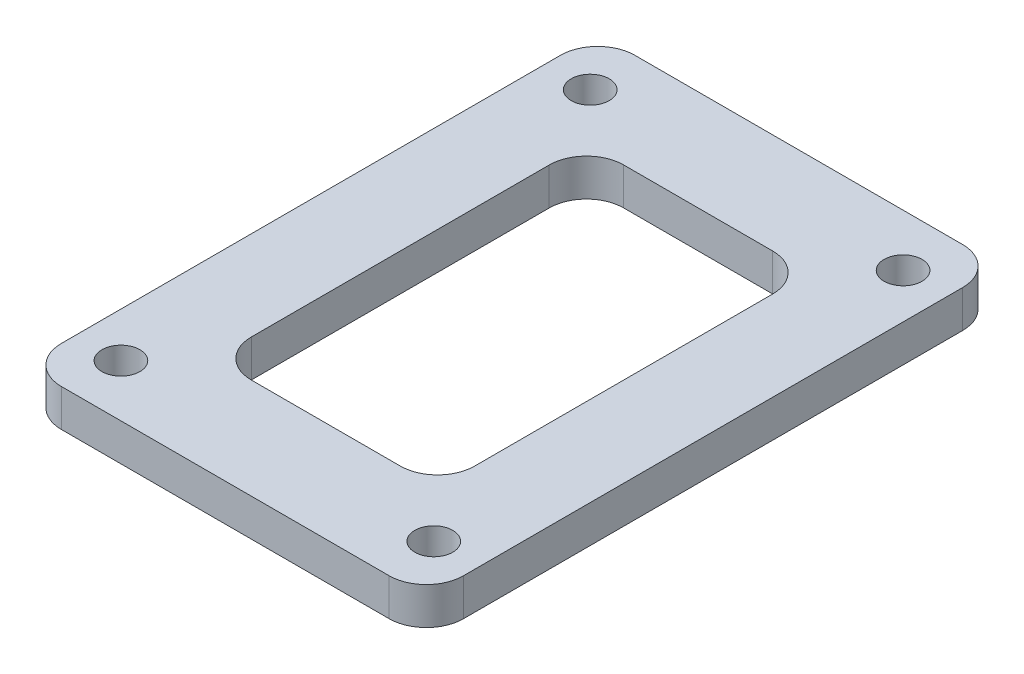
SolidWorks part; units mm, degrees
ref_plane "Front Plane" through (0, 0, 0) normal (0, 0, 1) x (1, 0, 0)
ref_plane "Top Plane" through (0, 0, 0) normal (0, 1, 0) x (1, 0, 0)
ref_plane "Right Plane" through (0, 0, 0) normal (1, 0, 0) x (0, 0, -1)
sketch "Sketch1" plane through (0, 0, 0) normal (0, 1, 0) x (1, 0, 0)
  line L1 (-27, 38.5) -> (27, 38.5)
  line L2 (-27, 38.5) -> (-27, -38.5)
  line L3 (-27, -38.5) -> (27, -38.5)
  line L4 (27, 38.5) -> (27, -38.5)
  line L5 (-27, 38.5) -> (27, -38.5) construction
  line L6 (-27, -38.5) -> (27, 38.5) construction
  point P0 (0, 0)
  dimension "D1" = 54
  dimension "D2" = 77
extrude "Boss-Extrude1" add sketch "Sketch1" along normal blind 5
sketch "Sketch2" plane through (0, 5, 0) normal (0, 1, 0) x (1, 0, 0)
  line L0 (27, 38.5) -> (-27, 38.5) construction
  line L1 (0, 38.5) -> (0, -38.5) construction
  line L2 (-27, -38.5) -> (27, -38.5) construction
  line L3 (-27, 0) -> (27, 0) construction
  line L4 (-27, 38.5) -> (-27, -38.5) construction
  line L5 (27, -38.5) -> (27, 38.5) construction
  circle A0 centre (-21, 31.5) radius 2.55
  dimension "D3" = 5.1
  dimension "D1" = 31.5
  dimension "D2" = 21
extrude "Cut-Extrude1" cut sketch "Sketch2" against normal through all
pattern_linear "LPattern1" count 2 spacing 42 along (1, 0, 0) count 2 spacing 63 along (0, 0, 1) of "Cut-Extrude1"
sketch "Sketch3" plane through (0, 5, 0) normal (0, 1, 0) x (1, 0, 0)
  line L1 (-15, -25) -> (15, -25)
  line L2 (-15, -25) -> (-15, 25)
  line L3 (-15, 25) -> (15, 25)
  line L4 (15, -25) -> (15, 25)
  line L5 (-15, -25) -> (15, 25) construction
  line L6 (-15, 25) -> (15, -25) construction
  point P0 (0, 0)
  dimension "D1" = 30
  dimension "D2" = 50
extrude "Cut-Extrude2" cut sketch "Sketch3" against normal through all
fillet "Fillet1" radius 5 8 edges at (27, 2.5, 38.5) (-27, 2.5, 38.5) (27, 2.5, -38.5) (-27, 2.5, -38.5) (-15, 2.5, 25) (15, 2.5, -25) (15, 2.5, 25) (-15, 2.5, -25)
